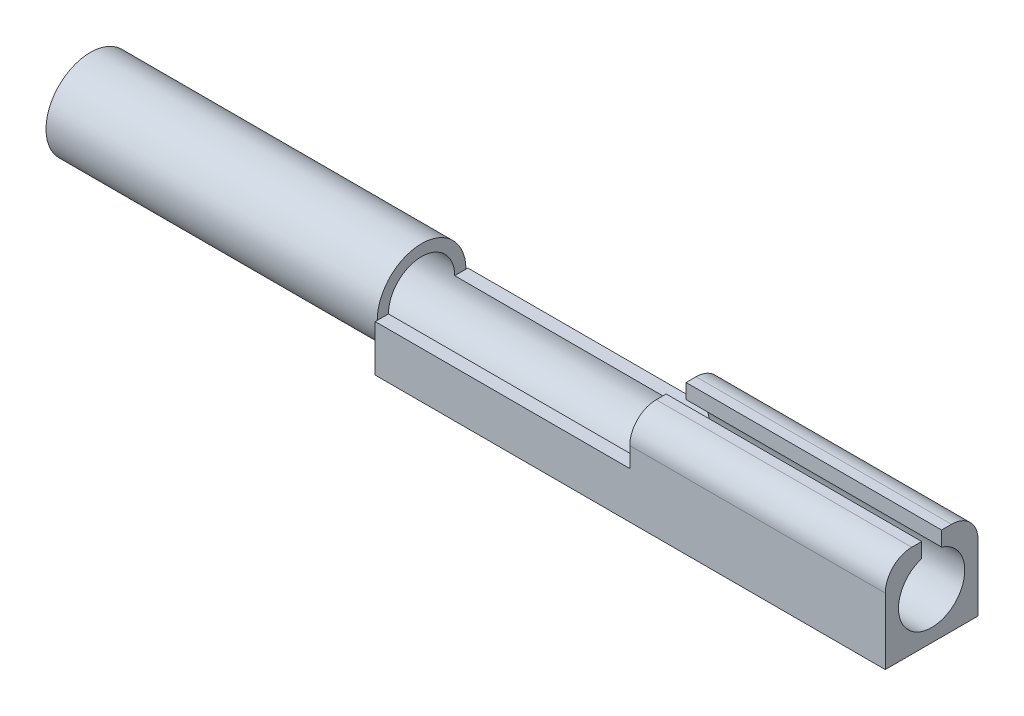
SolidWorks part; units mm, degrees
ref_plane "Спереди" through (0, 0, 0) normal (0, 0, 1) x (1, 0, 0)
ref_plane "Сверху" through (0, 0, 0) normal (0, 1, 0) x (1, 0, 0)
ref_plane "Справа" through (0, 0, 0) normal (1, 0, 0) x (0, 0, -1)
sketch "Эскиз1" plane through (0, 0, 0) normal (0, 0, 1) x (1, 0, 0)
  line L1 (0, 0) -> (12.7, 0)
  line L2 (0, 0) -> (0, 1.4)
  line L3 (0, 1.4) -> (12.7, 1.4)
  line L4 (12.7, 0) -> (12.7, 1.4)
  dimension "D1" = 12.7
  dimension "D2" = 1.4
extrude "Вытянуть1" add sketch "Эскиз1" along normal blind 1.4
sketch "Эскиз2" plane through (0, 0, 0) normal (-1, 0, 0) x (0, 0, 1)
  line L0 (0.7, 0.7) -> (0.7, 1.1992) construction
  line L1 (0.7, 0.7) -> (1.2352, 0.7) construction
  line L2 (0, 1.4) -> (0, 0) construction
  line L3 (1.4, 1.4) -> (1.4, 0) construction
  line L4 (1.4, 0) -> (0, 0) construction
  line L5 (1.4, 1.4) -> (0, 1.4) construction
  circle A0 centre (0.7, 0.7) radius 0.5
  dimension "D1" = 1
extrude "Вырез-Вытянуть1" cut sketch "Эскиз2" against normal blind 20
sketch "Эскиз3" plane through (0, 0, 0) normal (-1, 0, 0) x (0, 0, 1)
  line L1 (-0.0966, -0.0853) -> (1.4863, -0.0853)
  line L2 (-0.0966, -0.0853) -> (-0.0966, 1.4832)
  line L3 (-0.0966, 1.4832) -> (1.4863, 1.4832)
  line L4 (1.4863, -0.0853) -> (1.4863, 1.4832)
  circle A0 centre (0.7, 0.7) radius 0.6699
extrude "Вырез-Вытянуть2" cut sketch "Эскиз3" against normal blind 5
sketch "Эскиз4" plane through (0, 1.4, 0) normal (0, 1, 0) x (-1, 0, 0)
  line L0 (-11.1208, 0.7) -> (-6.6954, 0.7) construction
  line L1 (-5, -0.3836) -> (-8.8427, -0.3836)
  line L2 (-5, -0.3836) -> (-5, 1.9504)
  line L3 (-5, 1.9504) -> (-8.8427, 1.9504)
  line L4 (-8.8427, -0.3836) -> (-8.8427, 0.55)
  line L5 (-8.8427, 0.55) -> (-12.932, 0.55)
  line L7 (-8.8427, 0.85) -> (-12.932, 0.85)
  line L8 (-12.932, 0.55) -> (-12.932, 0.85)
  line L9 (-12.7, 0.7) -> (0, 0.7) construction
  line L10 (-12.7, 0) -> (-5, 0) construction
  line L11 (-12.7, 1.4) -> (-5, 1.4) construction
  line L12 (-8.8427, 0.85) -> (-8.8427, 1.9504)
  dimension "D1" = 0.3
extrude "Вырез-Вытянуть3" cut sketch "Эскиз4" against normal blind 0.7
fillet "Скругление1" radius 0.4
